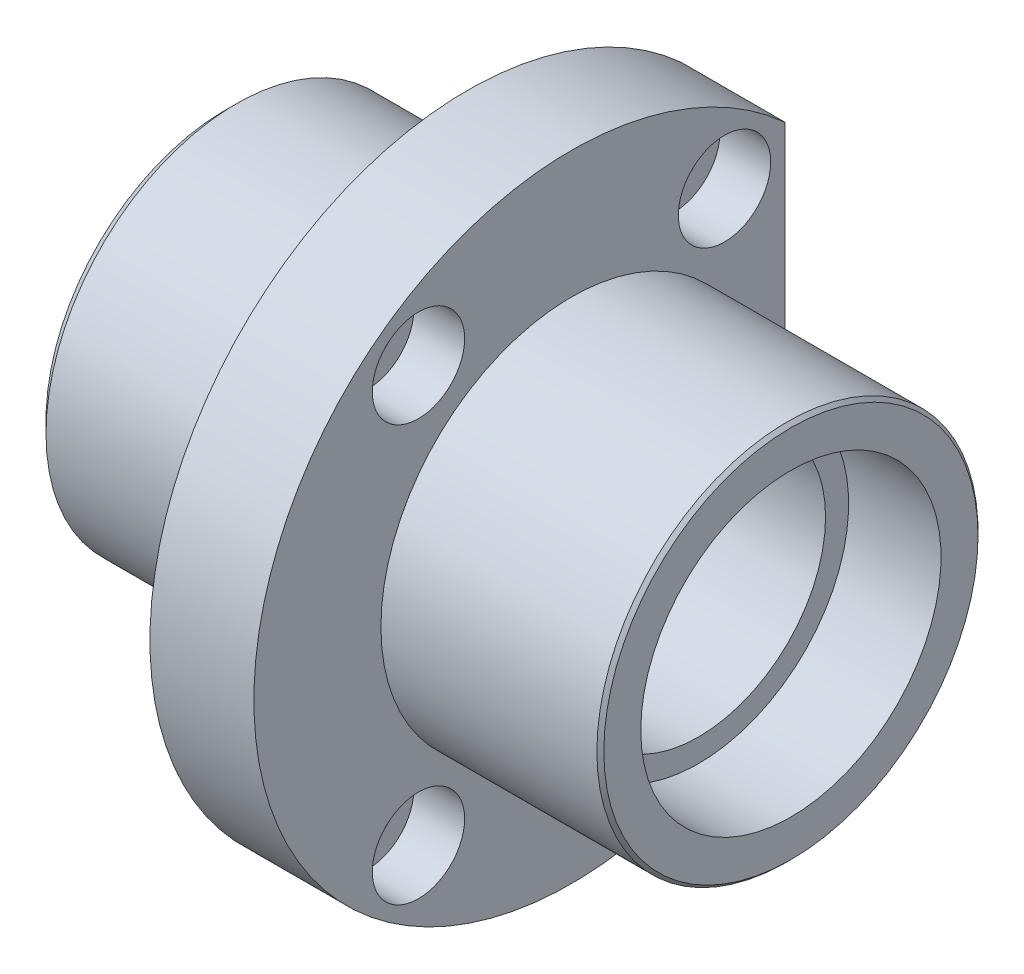
SolidWorks part; units mm, degrees
ref_plane "Front" through (0, 0, 0) normal (0, 0, 1) x (1, 0, 0)
ref_plane "Top" through (0, 0, 0) normal (0, 1, 0) x (1, 0, 0)
ref_plane "Right" through (0, 0, 0) normal (1, 0, 0) x (0, 0, -1)
sketch "Sketch1" plane through (0, 0, 0) normal (0, 0, 1) x (1, 0, 0)
  line L0 (-30.2028, 0) -> (34.471, 0) construction
  line L1 (-21, 0) -> (-21, 16.5)
  line L2 (-21, 16.5) -> (0, 16.5)
  line L3 (0, 16.5) -> (0, 27.5)
  line L4 (0, 27.5) -> (9, 27.5)
  line L5 (9, 27.5) -> (9, 16.5)
  line L6 (9, 16.5) -> (28, 16.5)
  line L7 (28, 16.5) -> (28, 0)
  line L8 (28, 0) -> (-21, 0)
  dimension "D1" = 55
  dimension "D2" = 33
  dimension "D3" = 21
  dimension "D4" = 9
  dimension "D5" = 28
revolve "Revolve1" add sketch "Sketch1" angle 360 about L0
sketch "Sketch2" plane through (0, 0, 0) normal (0, 0, 1) x (1, 0, 0)
  line L0 (-25.4914, 0) -> (31.0722, 0) construction
  line L1 (-21, 0) -> (-21, 13)
  line L2 (-21, 16.5) -> (-21, -16.5) construction
  line L3 (-21, 13) -> (-5, 13)
  line L4 (-5, 13) -> (-5, 11)
  line L5 (-5, 11) -> (20, 11)
  line L6 (20, 11) -> (20, 13)
  line L7 (20, 13) -> (28, 13)
  line L8 (28, -16.5) -> (28, 16.5) construction
  line L9 (28, 13) -> (28, 0)
  line L10 (28, 0) -> (-21, 0)
  line L11 (0, 16.5) -> (0, -16.5) construction
  line L12 (0, 27.5) -> (0, -27.5) construction
  dimension "D1" = 26
  dimension "D2" = 22
  dimension "D3" = 5
  dimension "D4" = 20
revolve "Cut-Revolve1" cut sketch "Sketch2" angle 360 about L0
sketch "Sketch5" plane through (9, 0, 0) normal (1, 0, 0) x (0, 0, -1)
  line L0 (18.5, 20.347) -> (18.5, -20.347)
  circle A0 centre (0, 0) radius 27.5 construction
  arc A1 (18.5, -20.347) -> (18.5, 20.347) centre (0, 0) ccw
  dimension "D1" = 18.5
extrude "Cut-Extrude1" cut sketch "Sketch5" against normal up to next
hole_wizard "CBORE for M4 Socket Head Cap Screw1" positions "Sketch4" profile "Sketch3" counterbore size "M4" standard "JIS" end condition through all
sketch "Sketch4" plane through (9, 0, 0) normal (1, 0, 0) x (0, 0, -1)
  line L0 (0, 34.8643) -> (0, -35.2836) construction
  line L2 (-32.1643, 0) -> (35.2535, 0) construction
  point P0 (-13.25, 18)
  point P1 (13.25, 18)
  point P3 (13.25, -18)
  point P5 (-13.25, -18)
  dimension "D1" = 26.5
  dimension "D2" = 36
sketch "Sketch3" plane through (9, 18, 13.25) normal (0, 1, 0) x (0, 0, -1)
  line L0 (0, 0) -> (0, 30)
  line L1 (0, 30) -> (2.25, 30)
  line L3 (2.25, 30) -> (2.25, 4.4)
  line L4 (2.25, 4.4) -> (4, 4.4)
  line L5 (4, 4.4) -> (4, 0)
  line L7 (4, 0) -> (0, 0)
  line L11 (0, -6.35) -> (0, 107.95) construction
  dimension "Thru Hole Dia." = 4.5
  dimension "Thru Hole Depth" = 30
  dimension "C'Bore Dia." = 8
  dimension "C'Bore Depth" = 4.4
chamfer "Chamfer1" distance 1 angle 45 1 edges at (-21, 0, 16.5)
chamfer "Chamfer2" distance 0.3 angle 45 1 edges at (28, 0, 16.5)
